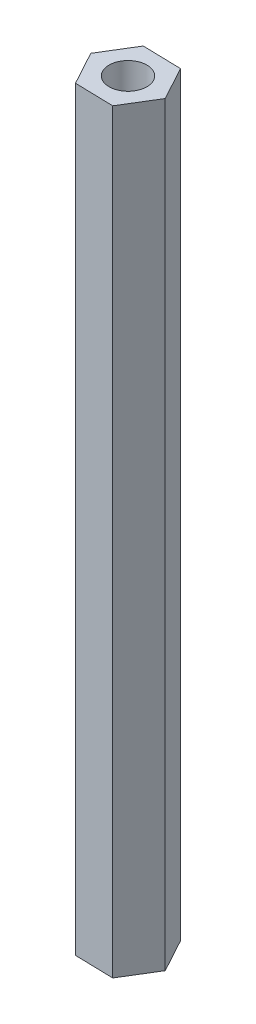
SolidWorks part; units mm, degrees
material "1023 Carbon Steel Sheet (SS)"
ref_plane "Front Plane" through (0, 0, 0) normal (0, 0, 1) x (1, 0, 0)
ref_plane "Top Plane" through (0, 0, 0) normal (0, 1, 0) x (1, 0, 0)
ref_plane "Right Plane" through (0, 0, 0) normal (1, 0, 0) x (0, 0, -1)
sketch "Sketch1" plane through (0, 0, 0) normal (0, 1, 0) x (1, 0, 0)
  line L1 (1.5834, 2.5882) -> (-1.4498, 2.6653)
  line L2 (-1.4498, 2.6653) -> (-3.0331, 0.0771)
  line L3 (-3.0331, 0.0771) -> (-1.5834, -2.5882)
  line L4 (-1.5834, -2.5882) -> (1.4498, -2.6653)
  line L5 (1.4498, -2.6653) -> (3.0331, -0.0771)
  line L6 (3.0331, -0.0771) -> (1.5834, 2.5882)
  circle A0 centre (0, 0) radius 1.5
  circle A1 centre (0, 0) radius 2.6276 construction
  dimension "D1" = 3
extrude "Boss-Extrude1" add sketch "Sketch1" along normal blind 60
